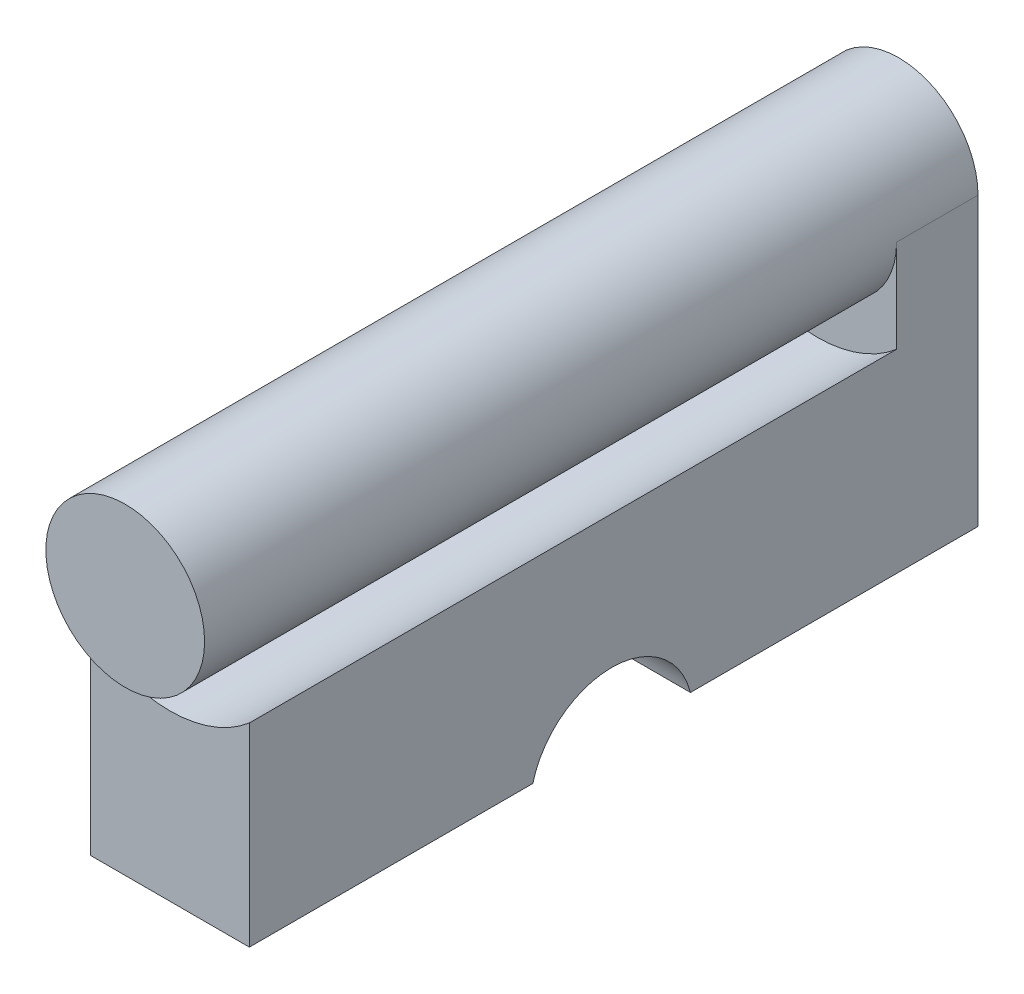
SolidWorks part; units mm, degrees
ref_plane "정면" through (0, 0, 0) normal (0, 0, 1) x (1, 0, 0)
ref_plane "윗면" through (0, 0, 0) normal (0, 1, 0) x (1, 0, 0)
ref_plane "우측면" through (0, 0, 0) normal (1, 0, 0) x (0, 0, -1)
sketch "스케치1" plane through (0, 0, 0) normal (0, 0, 1) x (1, 0, 0)
  circle A0 centre (0, 0) radius 1.95
  dimension "D1" = 3.9
extrude "보스-돌출1" add sketch "스케치1" along normal blind 19
sketch "스케치4" plane through (0, 0, 0) normal (1, 0, 0) x (0, 0, -1)
  line L5 (-2, 1.95) -> (0, 1.95)
  line L6 (-2, 1.95) -> (-2, -7.05)
  line L7 (-2, -7.05) -> (0, -7.05)
  line L8 (0, 1.95) -> (0, -7.05)
  line L9 (-2, 1.95) -> (0, -7.05) construction
  line L10 (-2, -7.05) -> (0, 1.95) construction
  point P0 (-1, -2.55)
  dimension "D1" = 2
  dimension "D2" = 9
extrude "보스-돌출2" add sketch "스케치4" along normal mid plane 3.9
sketch "스케치5" plane through (0, 0, 19) normal (0, 0, 1) x (1, 0, 0)
  line L0 (-1.95, 0) -> (-1.95, 1.95)
  line L1 (-1.95, 0) -> (-1.95, -7.05) construction
  line L2 (-1.95, 1.95) -> (1.95, 1.95)
  line L3 (1.95, 1.95) -> (1.95, 0)
  line L4 (1.95, 1.95) -> (1.95, 0) construction
  line L5 (1.95, 0) -> (1.95, 1.95)
  circle A0 centre (0, 0) radius 1.95 construction
  circle A1 centre (0, 0) radius 1.95
  circle M1 centre (0, 0) radius 1.95
extrude "컷-돌출1" cut sketch "스케치5" against normal through all contours L2 L0 M1 | L3 L2 M1
sketch "스케치8" plane through (0, 0, 2) normal (0, 0, 1) x (1, 0, 0)
  line L0 (-1.95, 0) -> (-1.95, -7.05)
  line L1 (-1.95, -7.05) -> (1.95, -7.05)
  line L2 (1.95, -7.05) -> (1.95, 0)
  line L3 (-1.95, -2.2798) -> (-1.95, -7.05)
  line L4 (1.95, -7.05) -> (1.95, -2.2798)
  line L6 (-1.95, 0) -> (-1.95, -7.05) construction
  circle A0 centre (0, 0) radius 1.95 construction
  circle A2 centre (0, 0) radius 1.95
  circle A3 centre (0, 0) radius 1.95
  arc A4 (-1.95, -2.2798) -> (1.95, -2.2798) centre (0, 0) ccw
  line M2 (1.95, -7.05) -> (1.95, 0)
  line M5 (-1.95, -7.05) -> (1.95, -7.05)
  dimension "D2" = 6
  dimension "D1" = 0
extrude "보스-돌출4" add sketch "스케치8" along normal blind 15.9 contours A4 L0 M5 M2
sketch "스케치9" plane through (-1.95, 0, 0) normal (-1, 0, 0) x (0, 0, 1)
  line L2 (19, -1.95) -> (19, 1.95) construction
  line L5 (17.9, -7.05) -> (0, -7.05) construction
  circle A0 centre (9, -7.55) radius 2
  dimension "D1" = 4
  dimension "D2" = 10
  dimension "D3" = 0.5
extrude "컷-돌출2" cut sketch "스케치9" against normal blind 17
equation "\"15.9.00mm\"=16"
